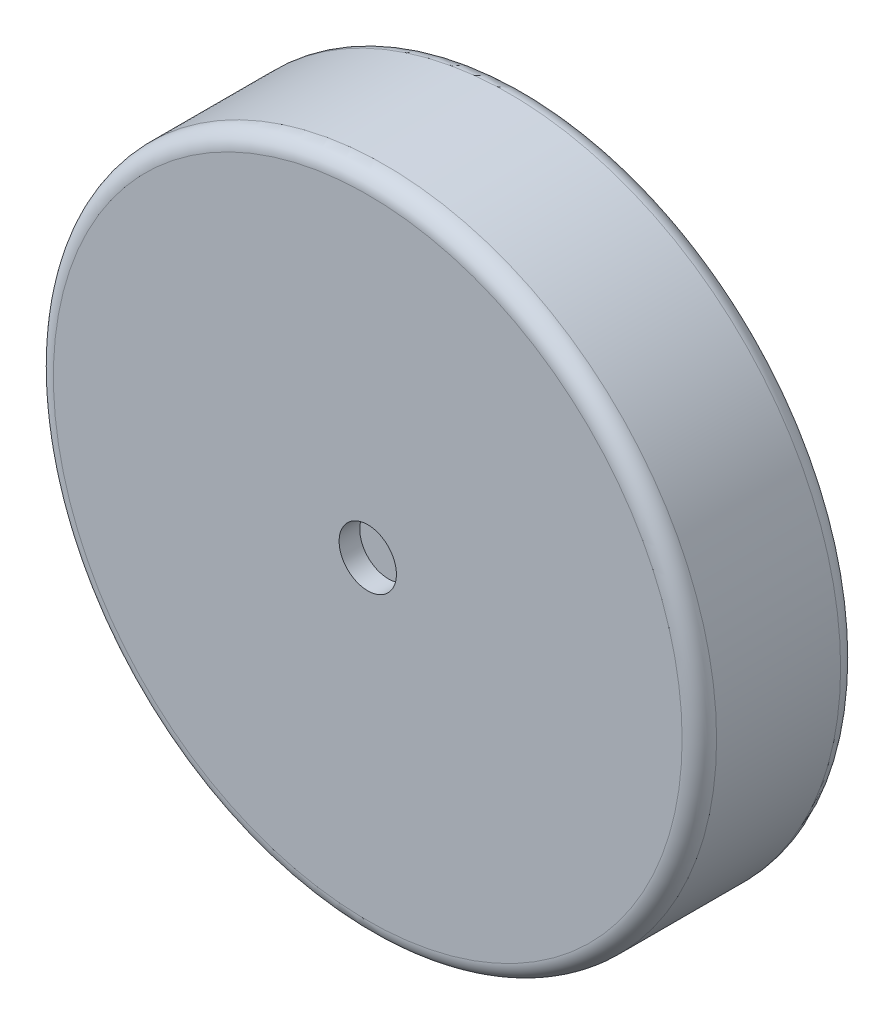
SolidWorks part; units mm, degrees
ref_plane "Front Plane" through (0, 0, 0) normal (0, 0, 1) x (1, 0, 0)
ref_plane "Top Plane" through (0, 0, 0) normal (0, 1, 0) x (1, 0, 0)
ref_plane "Right Plane" through (0, 0, 0) normal (1, 0, 0) x (0, 0, -1)
sketch "Sketch1" plane through (0, 0, 0) normal (0, 0, 1) x (1, 0, 0)
  circle A0 centre (0, 0) radius 48.895
  dimension "D1" = 97.79
extrude "Boss-Extrude1" add sketch "Sketch1" along normal blind 23.368
fillet "Fillet1" radius 2.54 1 edges at (48.895, 0, 23.368)
fillet "Fillet2" radius 2.54 1 edges at (48.895, 0, 0)
sketch "Sketch2" plane through (0, 0, 23.368) normal (0, 0, 1) x (1, 0, 0)
  circle A0 centre (0, 0) radius 4.2257
extrude "Cut-Extrude1" cut sketch "Sketch2" against normal blind 3.048
